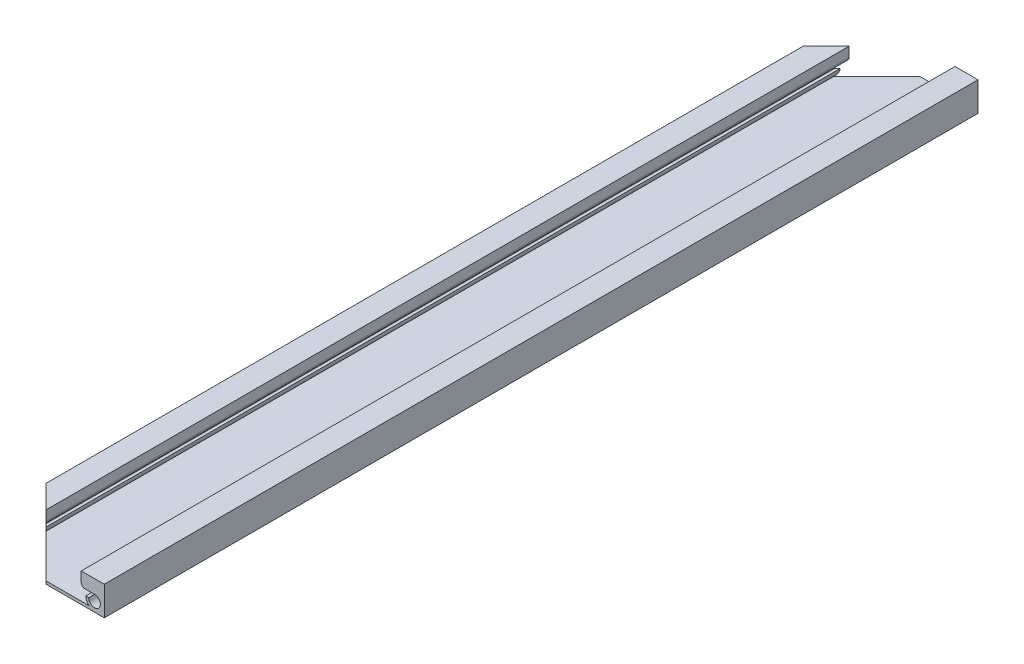
SolidWorks part; units mm, degrees
ref_plane "정면" through (0, 0, 0) normal (0, 0, 1) x (1, 0, 0)
ref_plane "윗면" through (0, 0, 0) normal (0, 1, 0) x (1, 0, 0)
ref_plane "우측면" through (0, 0, 0) normal (1, 0, 0) x (0, 0, -1)
sketch "스케치1" plane through (0, 0, 0) normal (0, 0, 1) x (1, 0, 0)
  line L1 (-30, 7.5) -> (30, 7.5)
  line L2 (-30, 7.5) -> (-30, -7.5)
  line L3 (-30, -7.5) -> (30, -7.5)
  line L4 (30, 7.5) -> (30, -7.5)
  line L5 (-30, 7.5) -> (30, -7.5) construction
  line L6 (-30, -7.5) -> (30, 7.5) construction
  point P0 (0, 0)
  dimension "D1" = 60
  dimension "D2" = 15
extrude "보스-돌출1" add sketch "스케치1" along normal blind 510
sketch "스케치2" plane through (0, 0, 0) normal (0, 0, -1) x (-1, 0, 0)
  line L0 (30, -7.5) -> (-30, -7.5) construction
  line L2 (-30, -7.5) -> (-30, 7.5) construction
  line L3 (30, 7.5) -> (30, -7.5) construction
  circle A0 centre (-25, -2.5) radius 3
  circle A1 centre (25, -2.5) radius 3
  dimension "D1" = 6
  dimension "D3" = 5
  dimension "D4" = 6
  dimension "D6" = 5
  dimension "D2" = 5
  dimension "D5" = 5
extrude "컷-돌출1" cut sketch "스케치2" against normal through all
sketch "스케치3" plane through (0, 0, 0) normal (0, 0, -1) x (-1, 0, 0)
  line L0 (-22.1716, -6) -> (22.1716, -6)
  line L1 (-20.5, -2.5) -> (-25, -2.5)
  line L2 (-25, -2.5) -> (-25, 0.5)
  line L3 (-25, 0.5) -> (25, 0.5)
  line L4 (25, 0.5) -> (25, -2.5)
  line L5 (25, -2.5) -> (20.5, -2.5)
  line L6 (30, -7.5) -> (-30, -7.5) construction
  arc A0 (22.1716, -6) -> (20.5, -2.5) centre (25, -2.5) cw
  arc A1 (-22.1716, -6) -> (-20.5, -2.5) centre (-25, -2.5) ccw
  circle A2 centre (-25, -2.5) radius 3 construction
  circle A3 centre (25, -2.5) radius 3 construction
  dimension "D2" = 1.5
  dimension "D1" = 1.5
  dimension "1.5" = 1.5
extrude "컷-돌출2" cut sketch "스케치3" against normal through all
sketch "스케치4" plane through (0, 0, 0) normal (0, 0, -1) x (-1, 0, 0)
  line L0 (-18.1431, 0.5) -> (18.1569, 0.5)
  line L1 (25, 0.5) -> (-25, 0.5) construction
  line L2 (-18.1431, 0.5) -> (-18.1431, 7.5)
  line L3 (-30, 7.5) -> (30, 7.5) construction
  line L4 (-18.1431, 7.5) -> (18.1569, 7.5)
  line L5 (18.1569, 7.5) -> (18.1569, 0.5)
  point P5 (0, 0)
  dimension "D1" = 36.3
extrude "컷-돌출3" cut sketch "스케치4" against normal through all
fillet "필렛1" radius 2 2 edges at (-18.1569, 0.5, 255) (18.1431, 0.5, 255)
sketch "스케치5" plane through (0, -7.5, 0) normal (0, -1, 0) x (1, 0, 0)
  line L0 (-30, 510) -> (-30, 450)
  line L1 (-30, 510) -> (-30, 0) construction
  line L2 (-30, 450) -> (30, 510)
  line L5 (-30, 0) -> (30, 0)
  line L6 (-30, 255) -> (30, 255) construction
  line L7 (30, 510) -> (30, 0) construction
  line L15 (-30, 510) -> (30, 510)
  line L17 (-30, 60) -> (30, 0)
  line L18 (-30, 0) -> (-30, 60)
  dimension "D1" = 45
extrude "컷-돌출4" cut sketch "스케치5" against normal through all
sketch "스케치7" plane through (0, -7.5, 0) normal (0, -1, 0) x (1, 0, 0)
  line L0 (-30, 450) -> (30, 510) construction
  line L1 (30, 0) -> (0, 0)
  line L2 (30, 0) -> (30, 30)
  line L3 (30, 30) -> (0, 30)
  line L4 (0, 0) -> (0, 30)
  line L5 (30, 510) -> (0, 510)
  line L6 (30, 510) -> (30, 480)
  line L7 (30, 480) -> (0, 480)
  line L8 (0, 510) -> (0, 480)
  dimension "D1" = 30
  dimension "D2" = 30
extrude "컷-돌출6" cut sketch "스케치7" against normal through all and the other way through all
